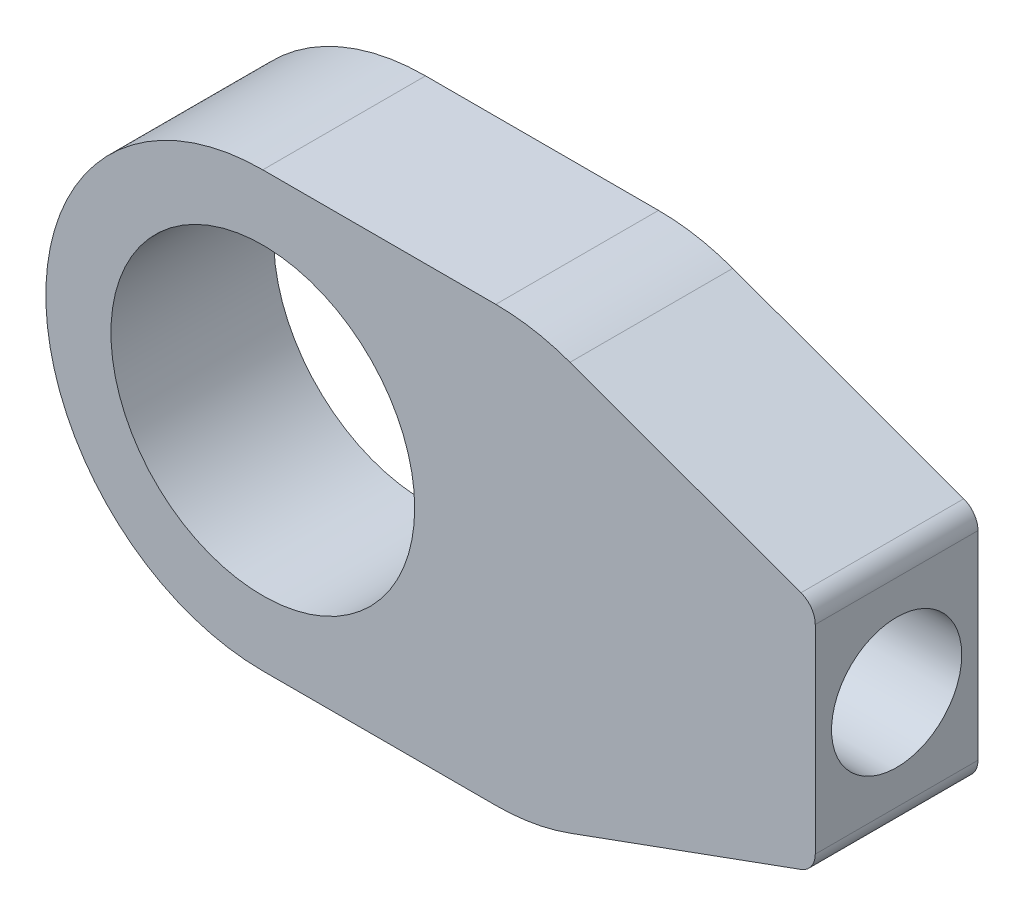
SolidWorks part; units mm, degrees
material "AISI 1020 Steel, Cold Rolled"
ref_plane "Front Plane" through (0, 0, 0) normal (0, 0, 1) x (1, 0, 0)
ref_plane "Top Plane" through (0, 0, 0) normal (0, 1, 0) x (1, 0, 0)
ref_plane "Right Plane" through (0, 0, 0) normal (1, 0, 0) x (0, 0, -1)
sketch "Sketch1" plane through (0, 0, 0) normal (0, 0, 1) x (1, 0, 0)
  line L10 (25.4605, -4.5826) -> (25.4605, 4.5826)
  line L11 (24.8025, 5.5223) -> (14.1569, 9.3969)
  line L12 (10.7367, 10) -> (0, 10)
  line L13 (0, -10) -> (10.7367, -10)
  line L14 (14.1569, -9.3969) -> (24.8025, -5.5223)
  circle A0 centre (0, 0) radius 7
  arc A10 (25.4605, 4.5826) -> (24.8025, 5.5223) centre (24.4605, 4.5826) ccw
  arc A11 (14.1569, 9.3969) -> (10.7367, 10) centre (10.7367, 0) ccw
  arc A12 (0, 10) -> (0, -10) centre (0, 0) ccw
  arc A13 (10.7367, -10) -> (14.1569, -9.3969) centre (10.7367, 0) ccw
  arc A14 (24.8025, -5.5223) -> (25.4605, -4.5826) centre (24.4605, -4.5826) ccw
  point P15 (25.4605, 0)
  dimension "D1" = 1
  dimension "D2" = 10
  dimension "D3" = 10
  dimension "D4" = 10
  dimension "D5" = 1
  dimension "D20" = 14
  dimension "D6" = 10.7367
  dimension "D7" = 10.7367
  dimension "D8" = 14.1569
  dimension "D9" = 14.1569
  dimension "D10" = 24.4605
  dimension "D11" = 24.4605
  dimension "D12" = 24.8025
  dimension "D13" = 24.8025
  dimension "D14" = 25.4605
  dimension "D15" = 25.4605
  dimension "D16" = 4.5826
  dimension "D17" = 9.3969
  dimension "D18" = 4.5826
  dimension "D19" = 9.3969
  dimension "D21" = 10.7367
  dimension "D22" = 10
extrude "Boss-Extrude1" add sketch "Sketch1" along normal blind 7.5
ref_plane "Plane1" through (25.4605, 0, 0) normal (1, 0, 0) x (0, 0, -1)
sketch "Sketch2" plane through (25.4605, 0, 0) normal (1, 0, 0) x (0, 0, -1)
  line L0 (-7.5, 10) -> (0, 10) construction
  circle A0 centre (-3.75, 0) radius 3
  point P8 (-3.75, 10)
  dimension "D1" = 6
extrude "Cut-Extrude1" cut sketch "Sketch2" against normal blind 10
